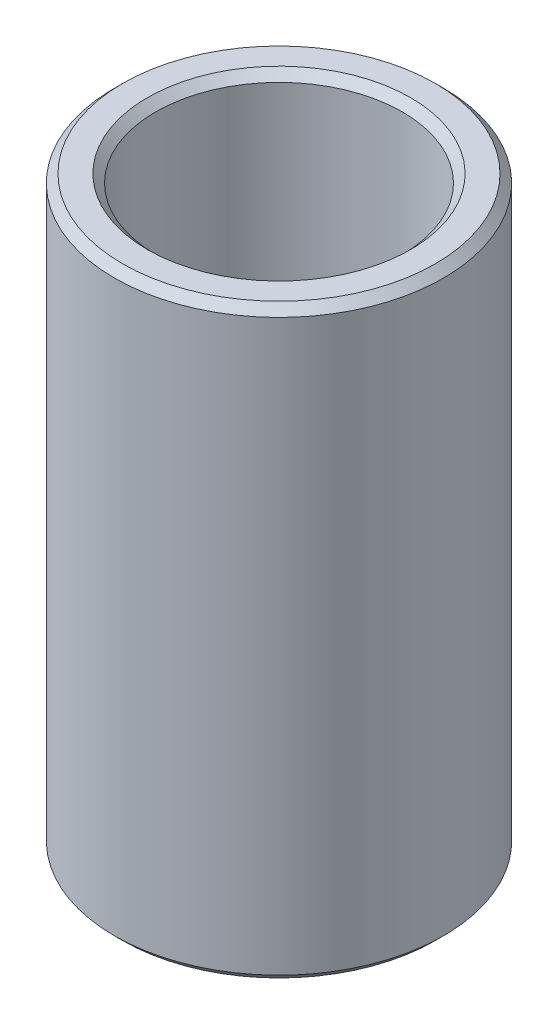
SolidWorks part; units mm, degrees
ref_plane "Front" through (0, 0, 0) normal (0, 0, 1) x (1, 0, 0)
ref_plane "Top" through (0, 0, 0) normal (0, 1, 0) x (1, 0, 0)
ref_plane "Right" through (0, 0, 0) normal (1, 0, 0) x (0, 0, -1)
sketch "Skizze1" plane through (0, 0, 0) normal (0, 1, 0) x (1, 0, 0)
  circle A0 centre (0, 0) radius 4
  circle A1 centre (0, 0) radius 3
  dimension "D1" = 8
  dimension "D2" = 6
extrude "Aufsatz-Linear austragen1" add sketch "Skizze1" along normal blind 14.25
chamfer "Fase1" distance 0.2 angle 45 4 edges at (0, 0, 4) (0, 14.25, 4) (0, 0, 3) (0, 14.25, 3)
